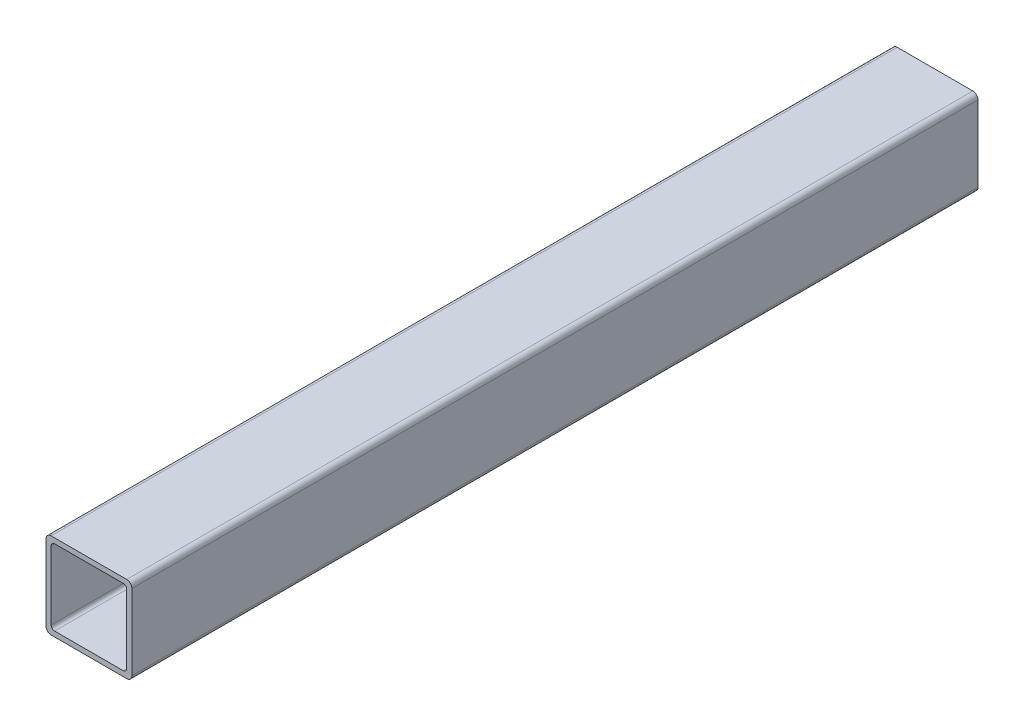
SolidWorks part; units mm, degrees
material "AISI 1020"
ref_plane "Спереди" through (0, 0, 0) normal (0, 0, 1) x (1, 0, 0)
ref_plane "Сверху" through (0, 0, 0) normal (0, 1, 0) x (1, 0, 0)
ref_plane "Справа" through (0, 0, 0) normal (1, 0, 0) x (0, 0, -1)
sketch "Эскиз1" plane through (0, 0, 0) normal (0, 0, 1) x (1, 0, 0)
  line L1 (0, 0) -> (0, 2145) construction
  point P0 (0, 0)
  point P2 (0, 0)
  line B0 (-22, 50) -> (22, 50)
  line B1 (-25, 47) -> (-25, 3)
  line B2 (-22, 0) -> (22, 0)
  line B3 (25, 47) -> (25, 3)
  line B4 (-20, 47) -> (20, 47)
  line B5 (-22, 45) -> (-22, 5)
  line B6 (-20, 3) -> (20, 3)
  line B7 (22, 45) -> (22, 5)
  arc B8 (-25, 3) -> (-22, 0) centre (-22, 3) ccw
  arc B9 (22, 0) -> (25, 3) centre (22, 3) ccw
  arc B10 (22, 50) -> (25, 47) centre (22, 47) cw
  arc B11 (-22, 50) -> (-25, 47) centre (-22, 47) ccw
  arc B12 (-22, 5) -> (-20, 3) centre (-20, 5) ccw
  arc B13 (20, 3) -> (22, 5) centre (20, 5) ccw
  arc B14 (20, 47) -> (22, 45) centre (20, 45) cw
  arc B15 (-20, 47) -> (-22, 45) centre (-20, 45) ccw
sketch_block_instance "Труба профильная 50х50х3-1"
sketch_block "Труба профильная 50х50х3" parameters "D3"=3, "D4"=2, "D1"=50, "D2"=3
extrude "Бобышка-Вытянуть1" add sketch "Эскиз1" against normal up to vertex (442.5 mm away)
